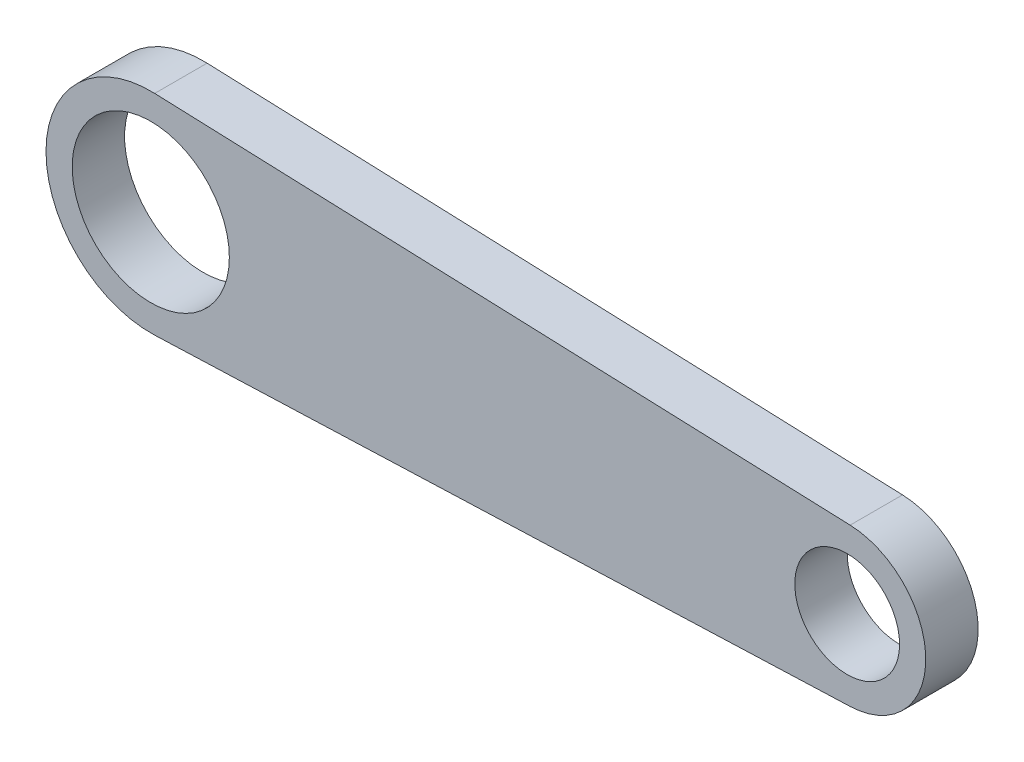
SolidWorks part; units mm, degrees
ref_plane "Front Plane" through (0, 0, 0) normal (0, 0, 1) x (1, 0, 0)
ref_plane "Top Plane" through (0, 0, 0) normal (0, 1, 0) x (1, 0, 0)
ref_plane "Right Plane" through (0, 0, 0) normal (1, 0, 0) x (0, 0, -1)
sketch "Sketch1" plane through (0, 0, 0) normal (0, 0, 1) x (1, 0, 0)
  line L4 (-66.47, 0) -> (66.47, 0) construction
  line L5 (-65.7178, 19.9858) -> (67.0342, 14.9894)
  line L6 (-65.7178, -19.9858) -> (67.0342, -14.9894)
  circle A2 centre (-66.47, 0) radius 15
  circle A3 centre (66.47, 0) radius 10
  arc A4 (-65.7178, 19.9858) -> (-65.7178, -19.9858) centre (-66.47, 0) ccw
  arc A6 (67.0342, -14.9894) -> (67.0342, 14.9894) centre (66.47, 0) ccw
  dimension "D3" = 20
  dimension "D4" = 5
  dimension "D1" = 30
  dimension "D2" = 5
  dimension "D6" = 20
  dimension "D7" = 15
  dimension "D5" = 132.94
extrude "Boss-Extrude1" add sketch "Sketch1" along normal blind 10
